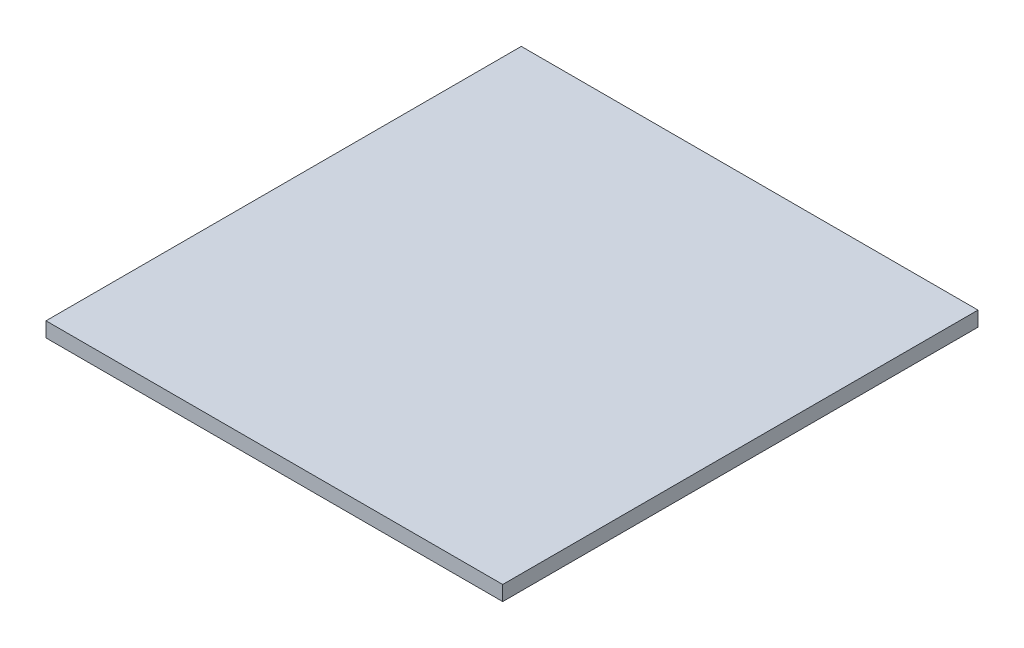
SolidWorks part; units mm, degrees
ref_plane "Front Plane" through (0, 0, 0) normal (0, 0, 1) x (1, 0, 0)
ref_plane "Top Plane" through (0, 0, 0) normal (0, 1, 0) x (1, 0, 0)
ref_plane "Right Plane" through (0, 0, 0) normal (1, 0, 0) x (0, 0, -1)
sketch "Sketch1" plane through (0, 0, 0) normal (0, 1, 0) x (1, 0, 0)
  line L1 (0, 406.4) -> (390.525, 406.4)
  line L2 (0, 406.4) -> (0, 0)
  line L3 (0, 0) -> (390.525, 0)
  line L4 (390.525, 406.4) -> (390.525, 0)
  line L5 (0, 406.4) -> (390.525, 0) construction
  line L6 (0, 0) -> (390.525, 406.4) construction
  point P0 (-2.6304, 18.4824)
  dimension "D1" = 406.4
  dimension "D2" = 390.525
extrude "Boss-Extrude1" add sketch "Sketch1" along normal blind 12.7
